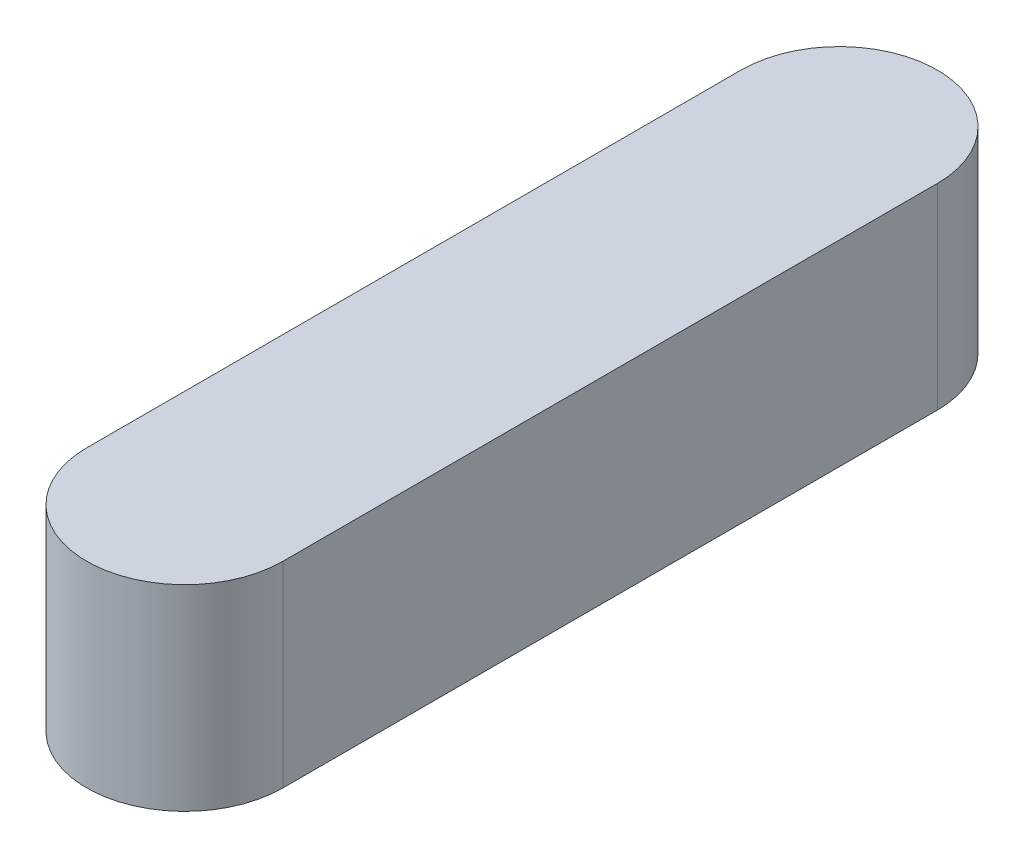
SolidWorks part; units mm, degrees
material "Plain Carbon Steel"
ref_plane "Front Plane" through (0, 0, 0) normal (0, 0, 1) x (1, 0, 0)
ref_plane "Top Plane" through (0, 0, 0) normal (0, 1, 0) x (1, 0, 0)
ref_plane "Right Plane" through (0, 0, 0) normal (1, 0, 0) x (0, 0, -1)
sketch "Sketch1" plane through (0, 0, 0) normal (0, 1, 0) x (1, 0, 0)
  line L0 (0, -10) -> (0, 10) construction
  line L2 (-3, 10) -> (-3, -10)
  line L4 (3, 10) -> (3, -10)
  arc A0 (3, 10) -> (-3, 10) centre (0, 10) ccw
  arc A1 (-3, -10) -> (3, -10) centre (0, -10) ccw
  dimension "D3" = 6
  dimension "D5" = 6
  dimension "D4" = 10
extrude "Boss-Extrude1" add sketch "Sketch1" along normal mid plane 6
sketch "Sketch2" plane through (0, 3, 0) normal (0, 1, 0) x (1, 0, 0)
  line L1 (-3, 13) -> (3, 13)
  line L2 (-3, 13) -> (-3, 10)
  line L3 (-3, 10) -> (3, 10)
  line L4 (3, 13) -> (3, 10)
  line L5 (-3, -10) -> (3, -10)
  line L6 (-3, -10) -> (-3, -13)
  line L7 (-3, -13) -> (3, -13)
  line L8 (3, -10) -> (3, -13)
  arc A0 (3, 10) -> (-3, 10) centre (0, 10) ccw construction
  arc A1 (-3, -10) -> (3, -10) centre (0, -10) ccw construction
extrude "Boss-Extrude2" [suppressed] add sketch "Sketch2" against normal up to surface (6 mm away)
other "Freeze***"
